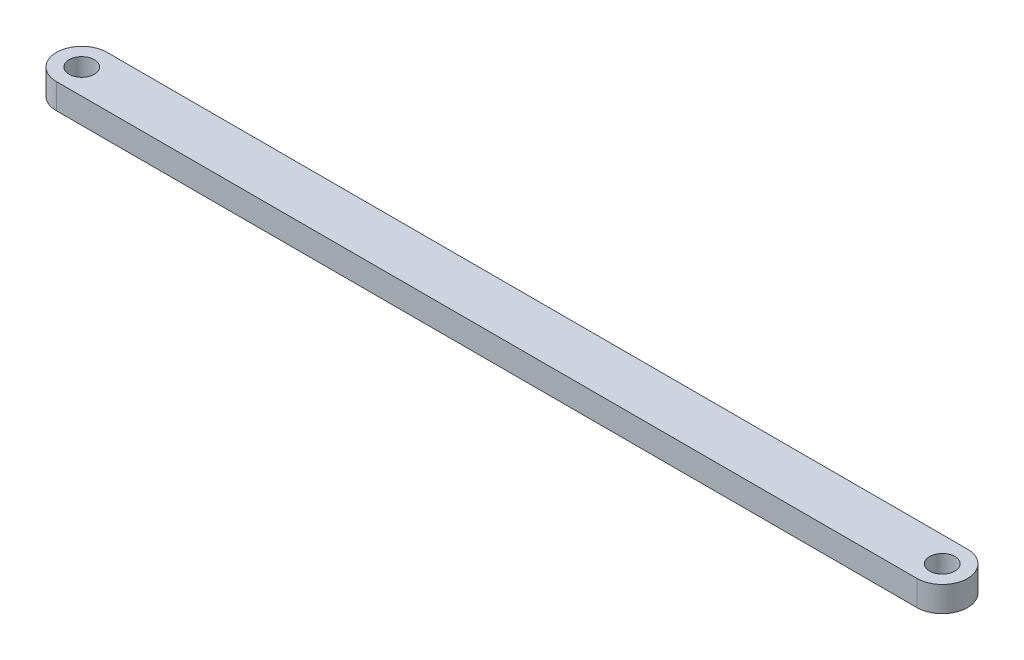
SolidWorks part; units mm, degrees
ref_plane "Front Plane" through (0, 0, 0) normal (0, 0, 1) x (1, 0, 0)
ref_plane "Top Plane" through (0, 0, 0) normal (0, 1, 0) x (1, 0, 0)
ref_plane "Right Plane" through (0, 0, 0) normal (1, 0, 0) x (0, 0, -1)
sketch "Sketch1" plane through (0, 0, 0) normal (0, 1, 0) x (1, 0, 0)
  line L1 (-85, 5) -> (85, 5)
  line L3 (-85, -5) -> (85, -5)
  arc A0 (-85, 5) -> (-85, -5) centre (-85, 0) ccw
  arc A1 (85, -5) -> (85, 5) centre (85, 0) ccw
  point P0 (0, 0)
  dimension "D3" = 10
  dimension "D4" = 10
  dimension "D1" = 170
  dimension "D2" = 10
extrude "Boss-Extrude1" add sketch "Sketch1" along normal blind 5
sketch "Sketch2" plane through (0, 5, 0) normal (0, 1, 0) x (1, 0, 0)
  circle A0 centre (-85, 0) radius 2.5
  circle A1 centre (85, 0) radius 2.5
  dimension "D1" = 5
  dimension "D2" = 5
extrude "Cut-Extrude1" cut sketch "Sketch2" against normal through all
